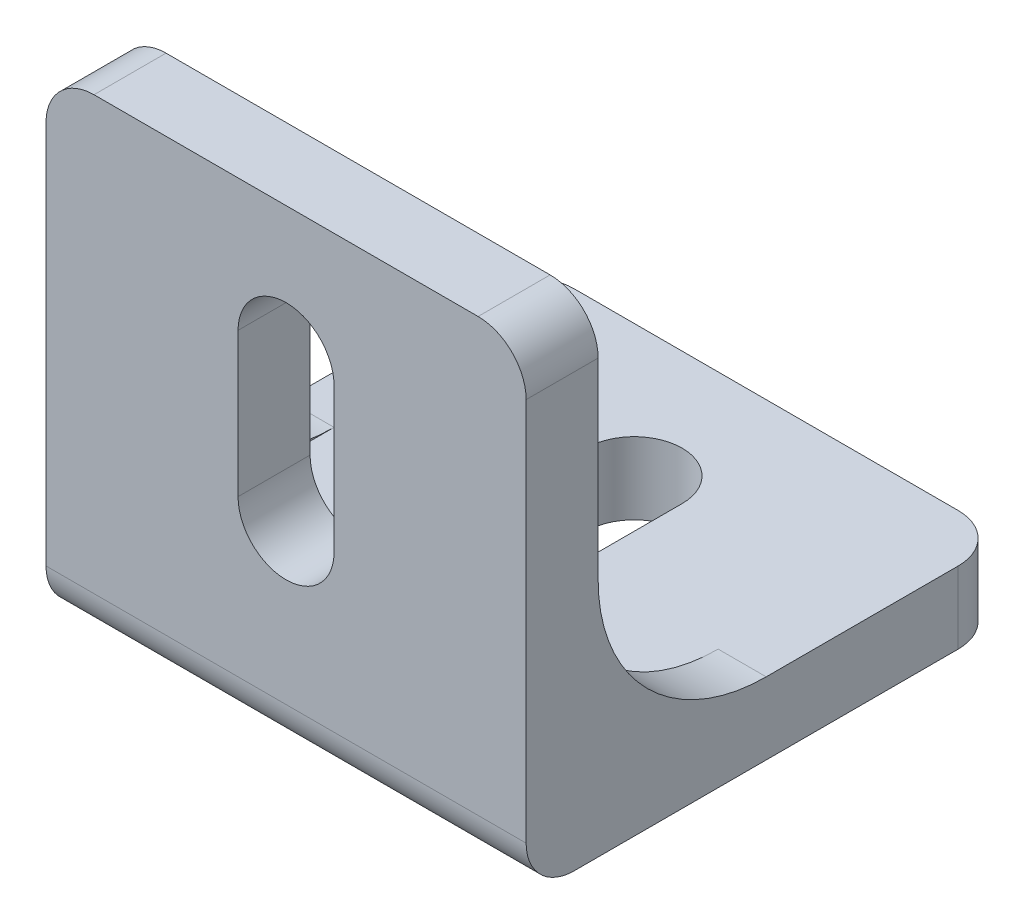
SolidWorks part; units mm, degrees
ref_plane "前视基准面" through (0, 0, 0) normal (0, 0, 1) x (1, 0, 0)
ref_plane "上视基准面" through (0, 0, 0) normal (0, 1, 0) x (1, 0, 0)
ref_plane "右视基准面" through (0, 0, 0) normal (1, 0, 0) x (0, 0, -1)
other "Configuration Table"
sketch "草图1" plane through (0, 0, 0) normal (1, 0, 0) x (0, 0, -1)
  line L0 (-7, 10) -> (-7, 0)
  line L1 (-10, -10) -> (10, -10)
  line L2 (-10, -10) -> (-10, 10)
  line L3 (-10, 10) -> (-7, 10)
  line L4 (10, -10) -> (10, -7)
  line L5 (-10, -10) -> (10, 10) construction
  line L6 (-10, 10) -> (10, -10) construction
  line L7 (0, -7) -> (10, -7)
  arc A0 (-7, 0) -> (0, -7) centre (0, 0) ccw
  point P0 (0, 0)
  dimension "D1" = 20
  dimension "D2" = 20
  dimension "D3" = 3
  dimension "D4" = 3
extrude "凸台-拉伸1" add sketch "草图1" against normal blind 20 contours L1 L4 L7 A0 L0 L3 L2
fillet "圆角1" radius 2 5 edges at (-10, -10, 10) (-20, -8.5, -10) (-20, 10, 8.5) (0, -8.5, -10) (0, 10, 8.5)
ref_plane "基准面1" through (-10, 0, 0) normal (-1, 0, 0) x (0, 0, 1)
sketch "草图2" plane through (-10, 0, 0) normal (-1, 0, 0) x (0, 0, 1)
  line L0 (7, 0) -> (7, -7)
  line L1 (7, -7) -> (0, -7)
  line L2 (0, -7) -> (0, 0)
  line L3 (0, 0) -> (7, 0)
extrude "切除-拉伸1" cut sketch "草图2" against normal mid plane 16
sketch "草图3" plane through (0, -7, 0) normal (0, 1, 0) x (1, 0, 0)
  line L1 (-18, 10) -> (-2, 10) construction
  line L3 (-12, 4.5) -> (-12, -1.5)
  line L4 (-8, 4.5) -> (-8, -1.5)
  arc A0 (-12, 4.5) -> (-8, 4.5) centre (-10, 4.5) cw
  arc A2 (-12, -1.5) -> (-8, -1.5) centre (-10, -1.5) ccw
  point P9 (-10, 6.5)
  dimension "D1" = 3.5
  dimension "D2" = 2
  dimension "D3" = 6
extrude "切除-拉伸4" cut sketch "草图3" against normal through all
sketch "草图6" plane through (0, 0, 7) normal (0, 0, -1) x (-1, 0, 0)
  line L0 (10, -9.9) -> (10, 9.9) construction
  line L1 (18, 10) -> (2, 10) construction
  line L2 (18, -7) -> (2, -7) construction
  line L3 (8, 4.5) -> (8, -1.5)
  line L4 (12, 4.5) -> (12, -1.5)
  arc A0 (12, 4.5) -> (8, 4.5) centre (10, 4.5) ccw
  arc A1 (8, -1.5) -> (12, -1.5) centre (10, -1.5) ccw
  dimension "D1" = 5.5
  dimension "D2" = 5.5
extrude "切除-拉伸5" cut sketch "草图6" against normal through all
